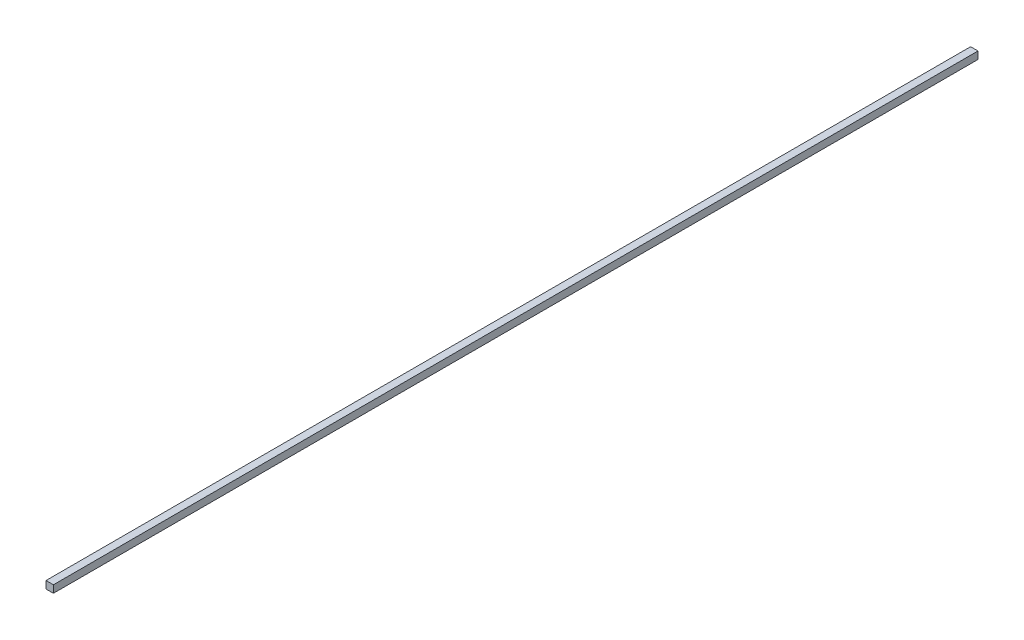
SolidWorks part; units mm, degrees
ref_plane "前基準面" through (0, 0, 0) normal (0, 0, 1) x (1, 0, 0)
ref_plane "上基準面" through (0, 0, 0) normal (0, 1, 0) x (1, 0, 0)
ref_plane "右基準面" through (0, 0, 0) normal (1, 0, 0) x (0, 0, -1)
sketch "草圖1" plane through (0, 0, 0) normal (0, 0, 1) x (1, 0, 0)
  line L1 (0, 0) -> (20, 0)
  line L2 (0, 0) -> (0, 20)
  line L3 (0, 20) -> (20, 20)
  line L4 (20, 0) -> (20, 20)
  dimension "D1" = 20
  dimension "D2" = 20
extrude "填料-伸長1" add sketch "草圖1" along normal blind 2500
